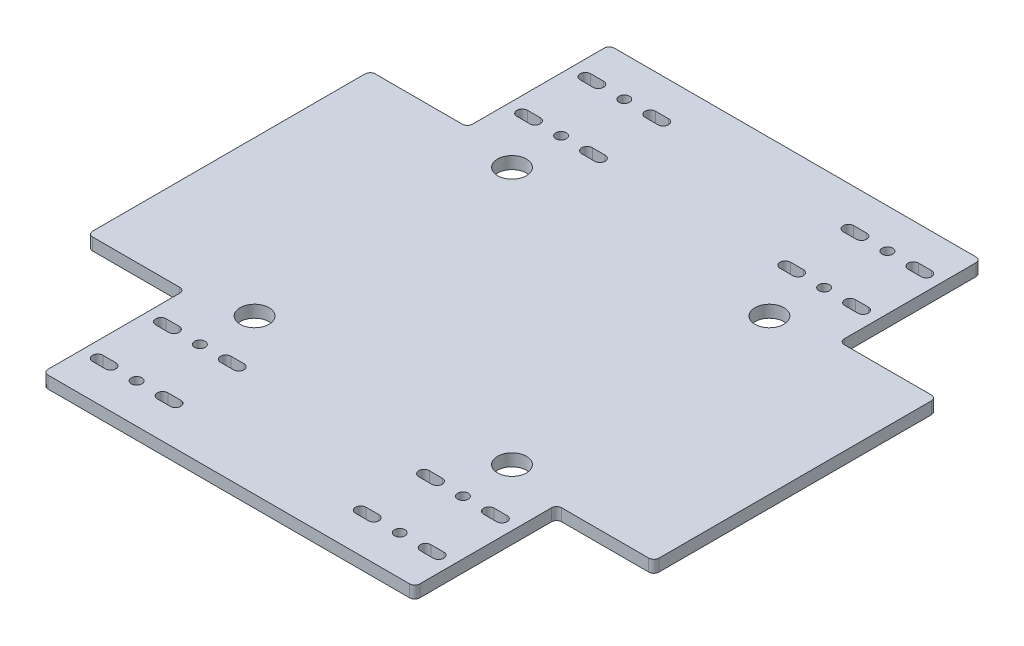
SolidWorks part; units mm, degrees
ref_plane "Front Plane" through (0, 0, 0) normal (0, 0, 1) x (1, 0, 0)
ref_plane "Top Plane" through (0, 0, 0) normal (0, 1, 0) x (1, 0, 0)
ref_plane "Right Plane" through (0, 0, 0) normal (1, 0, 0) x (0, 0, -1)
sketch "Sketch1" plane through (0, 0, 0) normal (0, 1, 0) x (1, 0, 0)
  line L1 (-139.7, -139.7) -> (139.7, -139.7)
  line L2 (-139.7, -139.7) -> (-139.7, 139.7)
  line L3 (-139.7, 139.7) -> (139.7, 139.7)
  line L4 (139.7, -139.7) -> (139.7, 139.7)
  line L5 (-139.7, -139.7) -> (139.7, 139.7) construction
  line L6 (-139.7, 139.7) -> (139.7, -139.7) construction
  point P0 (0, 0)
  dimension "D1" = 279.4
  dimension "D2" = 279.4
extrude "Boss-Extrude1" add sketch "Sketch1" along normal blind 5.9944
sketch "Sketch2" plane through (0, 5.9944, 0) normal (0, 1, 0) x (1, 0, 0)
  line L1 (-139.7, 139.7) -> (-91.7, 139.7)
  line L2 (-139.7, 139.7) -> (-139.7, 69.7)
  line L3 (-139.7, 69.7) -> (-91.7, 69.7)
  line L4 (-91.7, 139.7) -> (-91.7, 69.7)
  line L5 (139.7, 139.7) -> (91.7, 139.7)
  line L6 (139.7, 139.7) -> (139.7, 69.7)
  line L7 (139.7, 69.7) -> (91.7, 69.7)
  line L8 (91.7, 139.7) -> (91.7, 69.7)
  line L9 (-139.7, -139.7) -> (-91.7, -139.7)
  line L10 (-139.7, -139.7) -> (-139.7, -69.7)
  line L11 (-139.7, -69.7) -> (-91.7, -69.7)
  line L12 (-91.7, -139.7) -> (-91.7, -69.7)
  line L13 (139.7, -139.7) -> (91.7, -139.7)
  line L14 (139.7, -139.7) -> (139.7, -69.7)
  line L15 (139.7, -69.7) -> (91.7, -69.7)
  line L16 (91.7, -139.7) -> (91.7, -69.7)
  dimension "D1" = 48
  dimension "D2" = 70
  dimension "D3" = 48
  dimension "D4" = 70
  dimension "D5" = 70
  dimension "D6" = 48
  dimension "D7" = 70
  dimension "D8" = 48
extrude "Cut-Extrude1" cut sketch "Sketch2" against normal through all
sketch "Sketch3" plane through (0, 5.9944, 0) normal (0, 1, 0) x (1, 0, 0)
  line L0 (-84.1, 120.3) -> (-77.7, 120.3) construction
  line L1 (-84.1, 122.9) -> (-77.7, 122.9)
  line L2 (-84.1, 117.7) -> (-77.7, 117.7)
  line L3 (-52.1, 120.3) -> (-45.7, 120.3) construction
  line L4 (-52.1, 122.9) -> (-45.7, 122.9)
  line L5 (-52.1, 117.7) -> (-45.7, 117.7)
  line L6 (-84.1, 89.1) -> (-77.7, 89.1) construction
  line L7 (-84.1, 91.7) -> (-77.7, 91.7)
  line L8 (-84.1, 86.5) -> (-77.7, 86.5)
  line L9 (-52.1, 89.1) -> (-45.7, 89.1) construction
  line L10 (-52.1, 91.7) -> (-45.7, 91.7)
  line L11 (-52.1, 86.5) -> (-45.7, 86.5)
  line L12 (-139.7, 0) -> (139.7, 0) construction
  line L13 (-84.1, 120.3) -> (-45.7, 120.3) construction
  line L14 (-84.1, 120.3) -> (-84.1, 89.1) construction
  line L15 (-84.1, 89.1) -> (-45.7, 89.1) construction
  line L16 (-45.7, 120.3) -> (-45.7, 89.1) construction
  line L17 (-139.7, 69.7) -> (-139.7, -69.7) construction
  line L18 (139.7, -69.7) -> (139.7, 69.7) construction
  line L19 (0, 139.7) -> (0, -139.7) construction
  line L20 (91.7, 139.7) -> (-91.7, 139.7) construction
  line L21 (-91.7, -139.7) -> (91.7, -139.7) construction
  line L22 (45.7, 120.3) -> (45.7, 89.1) construction
  line L23 (84.1, 89.1) -> (45.7, 89.1) construction
  line L24 (84.1, 120.3) -> (84.1, 89.1) construction
  line L25 (84.1, 120.3) -> (45.7, 120.3) construction
  line L26 (52.1, 89.1) -> (45.7, 89.1) construction
  line L27 (52.1, 91.7) -> (45.7, 91.7)
  line L28 (52.1, 86.5) -> (45.7, 86.5)
  line L29 (84.1, 89.1) -> (77.7, 89.1) construction
  line L30 (84.1, 91.7) -> (77.7, 91.7)
  line L31 (84.1, 86.5) -> (77.7, 86.5)
  line L32 (52.1, 120.3) -> (45.7, 120.3) construction
  line L33 (52.1, 122.9) -> (45.7, 122.9)
  line L34 (52.1, 117.7) -> (45.7, 117.7)
  line L35 (84.1, 120.3) -> (77.7, 120.3) construction
  line L36 (84.1, 122.9) -> (77.7, 122.9)
  line L37 (84.1, 117.7) -> (77.7, 117.7)
  line L38 (-84.1, -120.3) -> (-77.7, -120.3) construction
  line L39 (-84.1, -122.9) -> (-77.7, -122.9)
  line L40 (-84.1, -117.7) -> (-77.7, -117.7)
  line L41 (-52.1, -120.3) -> (-45.7, -120.3) construction
  line L42 (-52.1, -122.9) -> (-45.7, -122.9)
  line L43 (-52.1, -117.7) -> (-45.7, -117.7)
  line L44 (-84.1, -89.1) -> (-77.7, -89.1) construction
  line L45 (-84.1, -91.7) -> (-77.7, -91.7)
  line L46 (-84.1, -86.5) -> (-77.7, -86.5)
  line L47 (-52.1, -89.1) -> (-45.7, -89.1) construction
  line L48 (-52.1, -91.7) -> (-45.7, -91.7)
  line L49 (-52.1, -86.5) -> (-45.7, -86.5)
  line L50 (52.1, -89.1) -> (45.7, -89.1) construction
  line L51 (52.1, -91.7) -> (45.7, -91.7)
  line L52 (52.1, -86.5) -> (45.7, -86.5)
  line L53 (84.1, -89.1) -> (77.7, -89.1) construction
  line L54 (84.1, -91.7) -> (77.7, -91.7)
  line L55 (84.1, -86.5) -> (77.7, -86.5)
  line L56 (52.1, -120.3) -> (45.7, -120.3) construction
  line L57 (52.1, -122.9) -> (45.7, -122.9)
  line L58 (52.1, -117.7) -> (45.7, -117.7)
  line L59 (84.1, -120.3) -> (77.7, -120.3) construction
  line L60 (84.1, -122.9) -> (77.7, -122.9)
  line L61 (84.1, -117.7) -> (77.7, -117.7)
  line L62 (84.1, -120.3) -> (45.7, -120.3) construction
  line L63 (84.1, -120.3) -> (84.1, -89.1) construction
  line L64 (84.1, -89.1) -> (45.7, -89.1) construction
  line L65 (45.7, -120.3) -> (45.7, -89.1) construction
  line L66 (-45.7, -120.3) -> (-45.7, -89.1) construction
  line L67 (-84.1, -89.1) -> (-45.7, -89.1) construction
  line L68 (-84.1, -120.3) -> (-84.1, -89.1) construction
  line L69 (-84.1, -120.3) -> (-45.7, -120.3) construction
  circle A0 centre (-45.7, 89.1) radius 1.6 construction
  circle A1 centre (-52.1, 89.1) radius 1.6 construction
  circle A2 centre (-58.5, 89.1) radius 1.6 construction
  circle A3 centre (-64.9, 89.1) radius 1.6 construction
  circle A4 centre (-77.7, 89.1) radius 1.6 construction
  circle A5 centre (-71.3, 89.1) radius 1.6 construction
  circle A6 centre (-84.1, 89.1) radius 1.6 construction
  circle A7 centre (-45.7, 120.3) radius 1.6 construction
  circle A8 centre (-52.1, 120.3) radius 1.6 construction
  circle A9 centre (-58.5, 120.3) radius 1.6 construction
  circle A10 centre (-64.9, 120.3) radius 1.6 construction
  circle A11 centre (-71.3, 120.3) radius 1.6 construction
  circle A12 centre (-77.7, 120.3) radius 1.6 construction
  circle A13 centre (-84.1, 120.3) radius 1.6 construction
  arc A14 (-84.1, 122.9) -> (-84.1, 117.7) centre (-84.1, 120.3) ccw
  arc A15 (-77.7, 117.7) -> (-77.7, 122.9) centre (-77.7, 120.3) ccw
  arc A16 (-52.1, 122.9) -> (-52.1, 117.7) centre (-52.1, 120.3) ccw
  arc A17 (-45.7, 117.7) -> (-45.7, 122.9) centre (-45.7, 120.3) ccw
  circle A18 centre (-64.9, 120.3) radius 2.6
  arc A19 (-84.1, 91.7) -> (-84.1, 86.5) centre (-84.1, 89.1) ccw
  arc A20 (-77.7, 86.5) -> (-77.7, 91.7) centre (-77.7, 89.1) ccw
  arc A21 (-52.1, 91.7) -> (-52.1, 86.5) centre (-52.1, 89.1) ccw
  arc A22 (-45.7, 86.5) -> (-45.7, 91.7) centre (-45.7, 89.1) ccw
  circle A23 centre (-64.9, 89.1) radius 2.6
  circle A24 centre (84.1, 120.3) radius 1.6 construction
  circle A25 centre (77.7, 120.3) radius 1.6 construction
  circle A26 centre (71.3, 120.3) radius 1.6 construction
  circle A27 centre (64.9, 120.3) radius 1.6 construction
  circle A28 centre (58.5, 120.3) radius 1.6 construction
  circle A29 centre (52.1, 120.3) radius 1.6 construction
  circle A30 centre (45.7, 120.3) radius 1.6 construction
  circle A31 centre (84.1, 89.1) radius 1.6 construction
  circle A32 centre (71.3, 89.1) radius 1.6 construction
  circle A33 centre (77.7, 89.1) radius 1.6 construction
  circle A34 centre (64.9, 89.1) radius 1.6 construction
  circle A35 centre (58.5, 89.1) radius 1.6 construction
  circle A36 centre (52.1, 89.1) radius 1.6 construction
  circle A37 centre (45.7, 89.1) radius 1.6 construction
  circle A38 centre (64.9, 89.1) radius 2.6
  circle A39 centre (64.9, 120.3) radius 2.6
  arc A40 (52.1, 91.7) -> (52.1, 86.5) centre (52.1, 89.1) cw
  arc A41 (45.7, 86.5) -> (45.7, 91.7) centre (45.7, 89.1) cw
  arc A42 (84.1, 91.7) -> (84.1, 86.5) centre (84.1, 89.1) cw
  arc A43 (77.7, 86.5) -> (77.7, 91.7) centre (77.7, 89.1) cw
  arc A44 (52.1, 122.9) -> (52.1, 117.7) centre (52.1, 120.3) cw
  arc A45 (45.7, 117.7) -> (45.7, 122.9) centre (45.7, 120.3) cw
  arc A46 (84.1, 122.9) -> (84.1, 117.7) centre (84.1, 120.3) cw
  arc A47 (77.7, 117.7) -> (77.7, 122.9) centre (77.7, 120.3) cw
  arc A48 (-84.1, -122.9) -> (-84.1, -117.7) centre (-84.1, -120.3) cw
  arc A49 (-77.7, -117.7) -> (-77.7, -122.9) centre (-77.7, -120.3) cw
  arc A50 (-52.1, -122.9) -> (-52.1, -117.7) centre (-52.1, -120.3) cw
  arc A51 (-45.7, -117.7) -> (-45.7, -122.9) centre (-45.7, -120.3) cw
  arc A52 (-84.1, -91.7) -> (-84.1, -86.5) centre (-84.1, -89.1) cw
  arc A53 (-77.7, -86.5) -> (-77.7, -91.7) centre (-77.7, -89.1) cw
  arc A54 (-52.1, -91.7) -> (-52.1, -86.5) centre (-52.1, -89.1) cw
  arc A55 (-45.7, -86.5) -> (-45.7, -91.7) centre (-45.7, -89.1) cw
  arc A56 (52.1, -91.7) -> (52.1, -86.5) centre (52.1, -89.1) ccw
  arc A57 (45.7, -86.5) -> (45.7, -91.7) centre (45.7, -89.1) ccw
  arc A58 (84.1, -91.7) -> (84.1, -86.5) centre (84.1, -89.1) ccw
  arc A59 (77.7, -86.5) -> (77.7, -91.7) centre (77.7, -89.1) ccw
  arc A60 (52.1, -122.9) -> (52.1, -117.7) centre (52.1, -120.3) ccw
  arc A61 (45.7, -117.7) -> (45.7, -122.9) centre (45.7, -120.3) ccw
  arc A62 (84.1, -122.9) -> (84.1, -117.7) centre (84.1, -120.3) ccw
  arc A63 (77.7, -117.7) -> (77.7, -122.9) centre (77.7, -120.3) ccw
  circle A64 centre (45.7, -89.1) radius 1.6 construction
  circle A65 centre (52.1, -89.1) radius 1.6 construction
  circle A66 centre (58.5, -89.1) radius 1.6 construction
  circle A67 centre (64.9, -89.1) radius 1.6 construction
  circle A68 centre (77.7, -89.1) radius 1.6 construction
  circle A69 centre (71.3, -89.1) radius 1.6 construction
  circle A70 centre (84.1, -89.1) radius 1.6 construction
  circle A71 centre (45.7, -120.3) radius 1.6 construction
  circle A72 centre (52.1, -120.3) radius 1.6 construction
  circle A73 centre (58.5, -120.3) radius 1.6 construction
  circle A74 centre (64.9, -120.3) radius 1.6 construction
  circle A75 centre (71.3, -120.3) radius 1.6 construction
  circle A76 centre (77.7, -120.3) radius 1.6 construction
  circle A77 centre (84.1, -120.3) radius 1.6 construction
  circle A78 centre (-84.1, -120.3) radius 1.6 construction
  circle A79 centre (-77.7, -120.3) radius 1.6 construction
  circle A80 centre (-71.3, -120.3) radius 1.6 construction
  circle A81 centre (-64.9, -120.3) radius 1.6 construction
  circle A82 centre (-58.5, -120.3) radius 1.6 construction
  circle A83 centre (-52.1, -120.3) radius 1.6 construction
  circle A84 centre (-45.7, -120.3) radius 1.6 construction
  circle A85 centre (-84.1, -89.1) radius 1.6 construction
  circle A86 centre (-71.3, -89.1) radius 1.6 construction
  circle A87 centre (-77.7, -89.1) radius 1.6 construction
  circle A88 centre (-64.9, -89.1) radius 1.6 construction
  circle A89 centre (-58.5, -89.1) radius 1.6 construction
  circle A90 centre (-52.1, -89.1) radius 1.6 construction
  circle A91 centre (-45.7, -89.1) radius 1.6 construction
  circle A92 centre (64.9, -120.3) radius 2.6
  circle A93 centre (64.9, -89.1) radius 2.6
  circle A94 centre (-64.9, -89.1) radius 2.6
  circle A95 centre (-64.9, -120.3) radius 2.6
  point P42 (-80.9, 120.3)
  point P47 (-48.9, 120.3)
  point P53 (-80.9, 89.1)
  point P58 (-48.9, 89.1)
  point P110 (48.9, 89.1)
  point P115 (80.9, 89.1)
  point P120 (48.9, 120.3)
  point P125 (80.9, 120.3)
  point P132 (-80.9, -120.3)
  point P139 (-48.9, -120.3)
  point P146 (-80.9, -89.1)
  point P153 (-48.9, -89.1)
  point P160 (48.9, -89.1)
  point P167 (80.9, -89.1)
  point P174 (48.9, -120.3)
  point P181 (80.9, -120.3)
  dimension "D1" = 3.2
  dimension "D2" = 1
  dimension "D3" = 1
  dimension "D4" = 1
  dimension "D5" = 1
  dimension "D6" = 1
  dimension "D7" = 1
extrude "Cut-Extrude2" cut sketch "Sketch3" against normal through all
fillet "Fillet1" radius 2.54 12 edges at (91.7, 2.9972, -139.7) (91.7, 2.9972, -69.7) (139.7, 2.9972, -69.7) (139.7, 2.9972, 69.7) (91.7, 2.9972, 69.7) (91.7, 2.9972, 139.7) (-91.7, 2.9972, 139.7) (-139.7, 2.9972, 69.7) (-91.7, 2.9972, 69.7) (-139.7, 2.9972, -69.7) (-91.7, 2.9972, -69.7) (-91.7, 2.9972, -139.7)
sketch "Sketch4" plane through (0, 5.9944, 0) normal (0, 1, 0) x (1, 0, 0)
  line L1 (63.5, -63.5) -> (-63.5, -63.5) construction
  line L2 (63.5, -63.5) -> (63.5, 63.5) construction
  line L3 (63.5, 63.5) -> (-63.5, 63.5) construction
  line L4 (-63.5, -63.5) -> (-63.5, 63.5) construction
  line L5 (63.5, -63.5) -> (-63.5, 63.5) construction
  line L6 (63.5, 63.5) -> (-63.5, -63.5) construction
  circle A0 centre (-63.5, 63.5) radius 7.125
  circle A1 centre (-63.5, -63.5) radius 7.125
  circle A2 centre (63.5, 63.5) radius 7.125
  circle A3 centre (63.5, -63.5) radius 7.125
  point P0 (0, 0)
  dimension "D3" = 14.25
  dimension "D4" = 14.25
  dimension "D5" = 14.25
  dimension "D6" = 14.25
  dimension "D1" = 127
  dimension "D2" = 127
extrude "Cut-Extrude3" cut sketch "Sketch4" against normal through all
